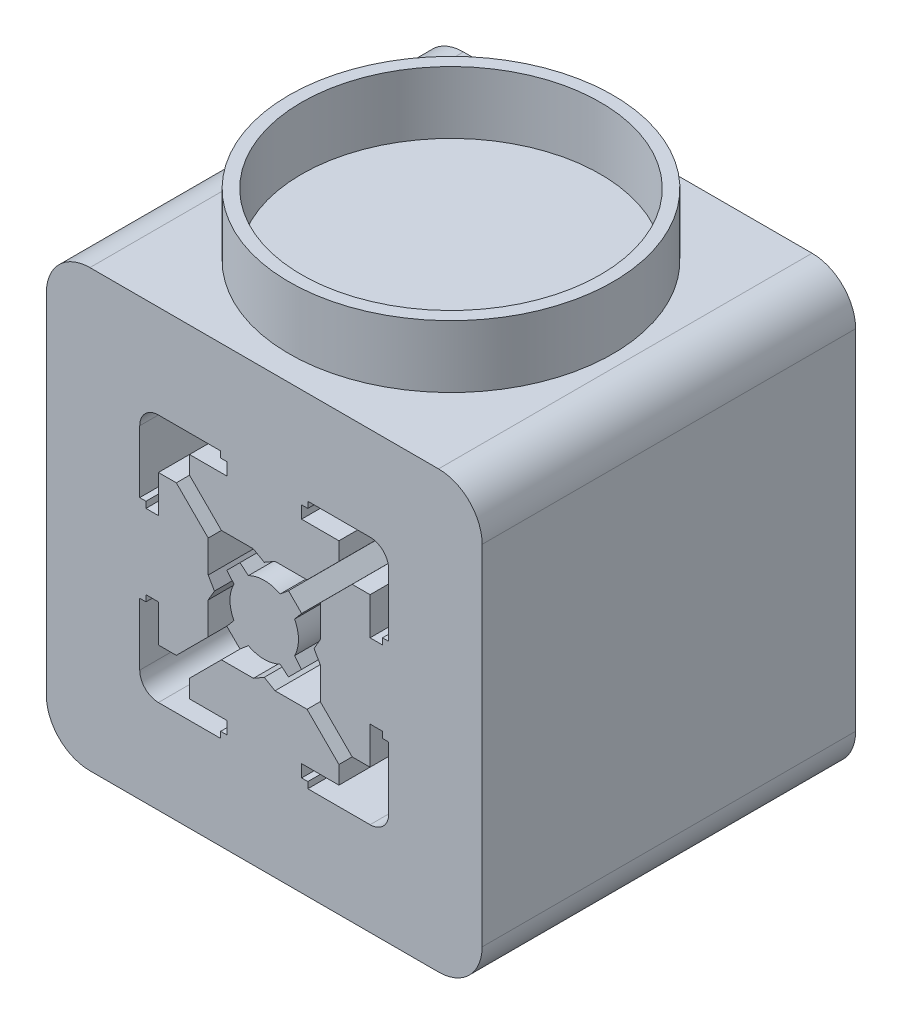
SolidWorks part; units mm, degrees
ref_plane "Plan de face" through (0, 0, 0) normal (0, 0, 1) x (1, 0, 0)
ref_plane "Plan de dessus" through (0, 0, 0) normal (0, 1, 0) x (1, 0, 0)
ref_plane "Plan de droite" through (0, 0, 0) normal (1, 0, 0) x (0, 0, -1)
sketch "Esquisse1" plane through (0, 0, 0) normal (0, 0, 1) x (1, 0, 0)
  line L0 (0, 0) -> (-4, 0) construction
  line L1 (-4, 0) -> (-4.5, 0.866)
  line L2 (-4, 0) -> (-4.5, -0.866)
  line L15 (-4.5, 0.866) -> (-4.5, 3.4393)
  line L16 (-4.5, 3.4393) -> (-7.0607, 6)
  line L17 (-7.0607, 6) -> (-8.5, 6)
  line L18 (-8.5, 6) -> (-8.5, 3)
  line L19 (-8.5, 3) -> (-9.5, 3)
  line L20 (-9.5, 3) -> (-9.5, 3.5)
  line L21 (-9.5, 3.5) -> (-10, 3.5)
  line L22 (-10, 3.5) -> (-10, 8.5)
  line L23 (0, 0) -> (0, 1.2745) construction
  line L24 (10, -3.5) -> (10, -8.5)
  line L25 (4.5, -3.4393) -> (7.0607, -6)
  line L26 (-9.5, -3.5) -> (-10, -3.5)
  line L27 (-9.5, -3) -> (-9.5, -3.5)
  line L28 (-8.5, -3) -> (-9.5, -3)
  line L29 (-8.5, -6) -> (-8.5, -3)
  line L30 (-7.0607, -6) -> (-8.5, -6)
  line L31 (-4.5, -0.866) -> (-4.5, -3.4393)
  line L32 (-4.5, -3.4393) -> (-7.0607, -6)
  line L33 (-10, -3.5) -> (-10, -8.5)
  line L34 (4.5, -0.866) -> (4.5, -3.4393)
  line L35 (7.0607, -6) -> (8.5, -6)
  line L36 (8.5, -6) -> (8.5, -3)
  line L37 (8.5, -3) -> (9.5, -3)
  line L38 (9.5, -3) -> (9.5, -3.5)
  line L39 (9.5, -3.5) -> (10, -3.5)
  line L40 (10, 3.5) -> (10, 8.5)
  line L41 (9.5, 3.5) -> (10, 3.5)
  line L42 (9.5, 3) -> (9.5, 3.5)
  line L43 (8.5, 3) -> (9.5, 3)
  line L44 (8.5, 6) -> (8.5, 3)
  line L45 (7.0607, 6) -> (8.5, 6)
  line L46 (4.5, 3.4393) -> (7.0607, 6)
  line L47 (4.5, 0.866) -> (4.5, 3.4393)
  line L48 (4, 0) -> (4.5, -0.866)
  line L49 (4, 0) -> (4.5, 0.866)
  line L50 (3.5, 10) -> (8.5, 10)
  line L51 (3.5, 9.5) -> (3.5, 10)
  line L52 (3, 8.5) -> (3, 9.5)
  line L53 (3, 9.5) -> (3.5, 9.5)
  line L54 (6, 8.5) -> (3, 8.5)
  line L55 (6, 7.0607) -> (6, 8.5)
  line L56 (3.4393, 4.5) -> (6, 7.0607)
  line L57 (0.866, 4.5) -> (3.4393, 4.5)
  line L58 (-0.866, 4.5) -> (-3.4393, 4.5)
  line L59 (-3.4393, 4.5) -> (-6, 7.0607)
  line L60 (-6, 7.0607) -> (-6, 8.5)
  line L61 (-6, 8.5) -> (-3, 8.5)
  line L62 (-3, 8.5) -> (-3, 9.5)
  line L63 (-3, 9.5) -> (-3.5, 9.5)
  line L64 (-3.5, 9.5) -> (-3.5, 10)
  line L65 (-3.5, 10) -> (-8.5, 10)
  line L66 (-14, 17.5) -> (14, 17.5)
  line L67 (9.5, -3.5) -> (10, -3.5)
  line L68 (8.5, -3) -> (9.5, -3)
  line L69 (9.5, -3) -> (9.5, -3.5)
  line L70 (8.5, -6) -> (8.5, -3)
  line L71 (7.0607, -6) -> (8.5, -6)
  line L72 (4.5, -3.4393) -> (7.0607, -6)
  line L73 (4.5, -0.866) -> (4.5, -3.4393)
  line L74 (4.5, 0.866) -> (4.5, 3.4393)
  line L75 (4.5, 3.4393) -> (7.0607, 6)
  line L76 (7.0607, 6) -> (8.5, 6)
  line L77 (8.5, 6) -> (8.5, 3)
  line L78 (8.5, 3) -> (9.5, 3)
  line L79 (9.5, 3) -> (9.5, 3.5)
  line L80 (9.5, 3.5) -> (10, 3.5)
  line L82 (-3.5, -10) -> (-8.5, -10)
  line L83 (-3.5, -9.5) -> (-3.5, -10)
  line L84 (-3, -8.5) -> (-3, -9.5)
  line L85 (-3, -9.5) -> (-3.5, -9.5)
  line L86 (-6, -8.5) -> (-3, -8.5)
  line L87 (-6, -7.0607) -> (-6, -8.5)
  line L88 (-3.4393, -4.5) -> (-6, -7.0607)
  line L89 (-0.866, -4.5) -> (-3.4393, -4.5)
  line L90 (0.866, -4.5) -> (3.4393, -4.5)
  line L91 (3.4393, -4.5) -> (6, -7.0607)
  line L92 (6, -7.0607) -> (6, -8.5)
  line L93 (6, -8.5) -> (3, -8.5)
  line L94 (3, -8.5) -> (3, -9.5)
  line L95 (3, -9.5) -> (3.5, -9.5)
  line L96 (3.5, -9.5) -> (3.5, -10)
  line L97 (3.5, -10) -> (8.5, -10)
  line L98 (0, 4) -> (0.866, 4.5)
  line L99 (0, 4) -> (-0.866, 4.5)
  line L100 (4, 0) -> (4.5, -0.866)
  line L101 (4, 0) -> (4.5, 0.866)
  line L102 (0, -4) -> (-0.866, -4.5)
  line L103 (0, -4) -> (0.866, -4.5)
  line L104 (0, 0) -> (-1.9002, -1.9879) construction
  line L105 (10, 3.5) -> (10, 10) [skipped]
  line L106 (10, -3.5) -> (10, -10) [skipped]
  line L108 (17.5, 14) -> (17.5, -14)
  line L109 (14, -17.5) -> (-14, -17.5)
  line L110 (-17.5, -14) -> (-17.5, 14)
  line L111 (1.9496, 3.0009) -> (1.2763, 2.4359)
  line L112 (-3.0009, 1.9496) -> (-2.4359, 1.2763)
  line L113 (-1.9473, 3.0032) -> (-1.2732, 2.4375)
  line L114 (-3.0009, 1.9496) -> (-1.9473, 3.0032)
  line L115 (1.9496, 3.0009) -> (3.0032, 1.9473)
  line L116 (3.0032, 1.9473) -> (2.4375, 1.2732)
  line L117 (3.0009, -1.9496) -> (2.4359, -1.2763)
  line L118 (3.0009, -1.9496) -> (1.9473, -3.0032)
  line L119 (1.9473, -3.0032) -> (1.2732, -2.4375)
  line L120 (-1.9496, -3.0009) -> (-1.2763, -2.4359)
  line L121 (-1.9496, -3.0009) -> (-3.0032, -1.9473)
  line L122 (-3.0032, -1.9473) -> (-2.4375, -1.2732)
  line L123 (0, 0) -> (-31.5064, 0) construction
  arc A0 (-10, 8.5) -> (-8.5, 10) centre (-8.5, 8.5) cw
  arc A1 (-10, -8.5) -> (-8.5, -10) centre (-8.5, -8.5) ccw
  arc A2 (10, -8.5) -> (8.5, -10) centre (8.5, -8.5) cw
  arc A3 (10, 8.5) -> (8.5, 10) centre (8.5, 8.5) ccw
  circle A4 centre (0, 0) radius 2.75
  arc A5 (-14, 17.5) -> (-17.5, 14) centre (-14, 14) ccw
  arc A6 (17.5, 14) -> (14, 17.5) centre (14, 14) ccw
  arc A7 (14, -17.5) -> (17.5, -14) centre (14, -14) ccw
  arc A8 (-17.5, -14) -> (-14, -17.5) centre (-14, -14) ccw
  arc A9 (-2.4359, 1.2763) -> (-2.4375, -1.2732) centre (0, 0) ccw
  arc A10 (1.2763, 2.4359) -> (-1.2732, 2.4375) centre (0, 0) ccw
  arc A11 (2.4359, -1.2763) -> (2.4375, 1.2732) centre (0, 0) ccw
  arc A12 (-1.2763, -2.4359) -> (1.2732, -2.4375) centre (0, 0) ccw
  point P43 (-10, 10)
  point P98 (0, 0)
  point P101 (-10, -10)
  point P102 (10, -10)
  point P106 (0, 0)
  point P107 (10, 10)
  point P109 (-5.7803, 4.7197)
  point P116 (0, 17.5)
  point P130 (-34.8338, 9.6149)
  point P135 (0, 0)
  point P146 (-32.3589, 7.14)
  dimension "D15" = 1.5
  dimension "D16" = 1.5
  dimension "D14" = 1.5
  dimension "D17" = 5.5
  dimension "D23" = 7.5
  dimension "D2" = 120
  dimension "D3" = 1
  dimension "D5" = 20
  dimension "D6" = 6
  dimension "D7" = 12
  dimension "D8" = 135
  dimension "D9" = 5.5
  dimension "D10" = 4
  dimension "D11" = 0.5
  dimension "D12" = 4
  dimension "D13" = 0.5
  dimension "D18" = 4
  dimension "D19" = 4.5
  dimension "D20" = 28
  dimension "D21" = 4
  dimension "D4" = 1.5
  dimension "D22" = 4
extrude "Boss.-Extru.1" add sketch "Esquisse1" along normal blind 30 contours A1 L82 L83 L85 L84 L86 L87 L88 L89 L102 L103 L90 L91 L92 L93 L94 L95 L96 L97 A2 L24 L39 L38 L37 L36 L35 L25 L34 L48 L49 L47 L46 L45 L44 L43 L42 L41 L40 A3 L50 L51 L53 L52 L54 L55 L56 L57 L98 L99 L58 L59 L60 L61 L62 L63 L64 L65 A0 L22 L21 L20 L19 L18 L17 L16 L15 L1 L2 L31 L32 L30 L29 L28 L27 L26 L33 | L66 A6 L108 A7 L109 A8 L110 A5 | A4
sketch "Esquisse3" plane through (0, 17.5, 0) normal (0, 1, 0) x (1, 0, 0)
  line L0 (0, 0) -> (0, -30) construction
  line L1 (-14, -30) -> (14, -30) construction
  line L2 (-14, -15) -> (14, -15) construction
  line L3 (-14, -30) -> (-14, 0) construction
  line L4 (14, -30) -> (14, 0) construction
  circle A0 centre (0, -15) radius 12
  circle A1 centre (0, -15) radius 13
  dimension "D1" = 24
  dimension "D2" = 26
extrude "Boss.-Extru.2" add sketch "Esquisse3" along normal blind 5
sketch "Esquisse4" plane through (0, 0, 30) normal (0, 0, 1) x (1, 0, 0)
  line L0 (1.9496, 3.0009) -> (1.2763, 2.4359)
  line L1 (-3.0009, 1.9496) -> (-2.4359, 1.2763)
  line L2 (-1.9473, 3.0032) -> (-1.2732, 2.4375)
  line L3 (-3.0009, 1.9496) -> (-1.9473, 3.0032)
  line L4 (1.9496, 3.0009) -> (3.0032, 1.9473)
  line L5 (3.0032, 1.9473) -> (2.4375, 1.2732)
  line L6 (3.0009, -1.9496) -> (2.4359, -1.2763)
  line L7 (3.0009, -1.9496) -> (1.9473, -3.0032)
  line L8 (1.9473, -3.0032) -> (1.2732, -2.4375)
  line L9 (-1.9496, -3.0009) -> (-1.2763, -2.4359)
  line L10 (-1.9496, -3.0009) -> (-3.0032, -1.9473)
  line L11 (-3.0032, -1.9473) -> (-2.4375, -1.2732)
  arc A0 (-2.4359, 1.2763) -> (-2.4375, -1.2732) centre (0, 0) ccw
  arc A1 (1.2763, 2.4359) -> (-1.2732, 2.4375) centre (0, 0) ccw
  arc A2 (2.4359, -1.2763) -> (2.4375, 1.2732) centre (0, 0) ccw
  arc A3 (-1.2763, -2.4359) -> (1.2732, -2.4375) centre (0, 0) ccw
  point P2 (0, 0)
  point P5 (0, 0)
  point P21 (0, 0)
extrude "Boss.-Extru.3" add sketch "Esquisse4" against normal up to surface (30 mm away) up to face at (0, 0, 0)
